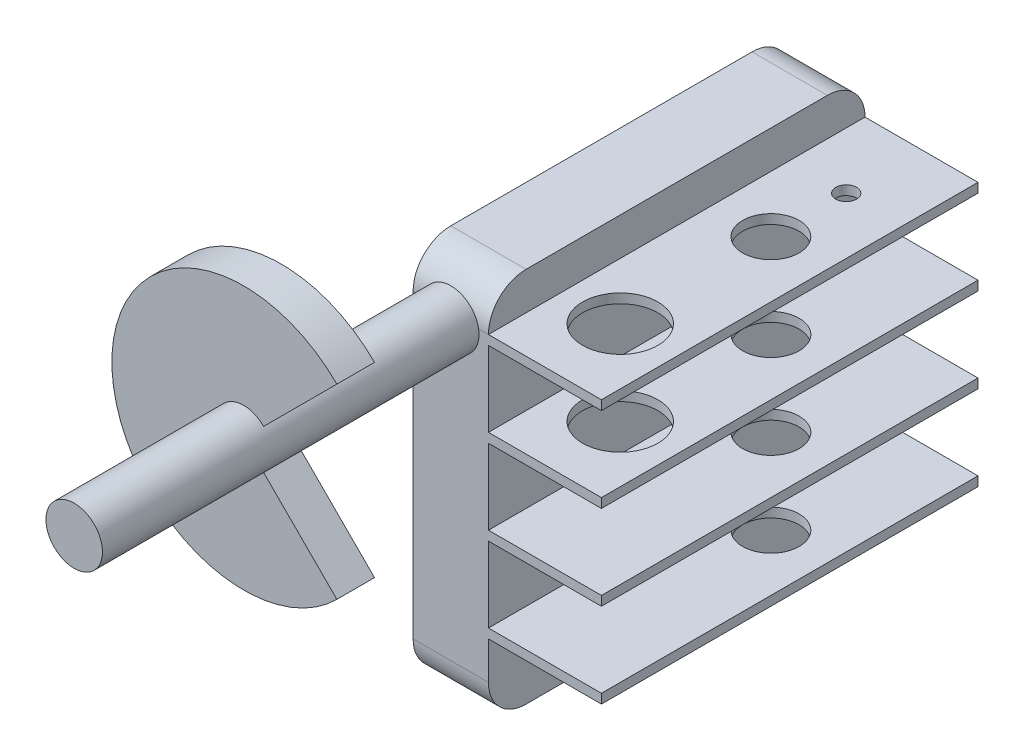
SolidWorks part; units mm, degrees
ref_plane "Front Plane" through (0, 0, 0) normal (0, 0, 1) x (1, 0, 0)
ref_plane "Top Plane" through (0, 0, 0) normal (0, 1, 0) x (1, 0, 0)
ref_plane "Right Plane" through (0, 0, 0) normal (1, 0, 0) x (0, 0, -1)
sketch "Sketch1" plane through (0, 0, 0) normal (0, 0, 1) x (1, 0, 0)
  line L0 (0, 0) -> (0, 10)
  line L1 (0, 10) -> (2, 10)
  line L2 (2, 10) -> (2, 9)
  line L3 (2, 0) -> (0, 0)
  line L4 (2, 8.75) -> (2, 6.75)
  line L5 (2, 9) -> (5, 9)
  line L7 (2, 8.75) -> (5, 8.75)
  line L8 (5, 9) -> (5, 8.75)
  line L9 (2, 6.75) -> (5, 6.75)
  line L11 (2, 6.5) -> (5, 6.5)
  line L12 (5, 6.75) -> (5, 6.5)
  line L13 (2, 4.5) -> (5, 4.5)
  line L15 (2, 4.25) -> (5, 4.25)
  line L16 (5, 4.5) -> (5, 4.25)
  line L17 (2, 2.25) -> (5, 2.25)
  line L19 (2, 2) -> (5, 2)
  line L20 (5, 2.25) -> (5, 2)
  line L21 (2, 6.5) -> (2, 4.5)
  line L22 (2, 4.25) -> (2, 2.25)
  line L23 (2, 2) -> (2, 0)
  dimension "D1" = 10
  dimension "D2" = 2
  dimension "D3" = 3
  dimension "D4" = 0.25
  dimension "D5" = 2
  dimension "D6" = 2
  dimension "D7" = 2
  dimension "D8" = 2
extrude "Boss-Extrude1" add sketch "Sketch1" along normal blind 10
fillet "Fillet1" radius 1 4 edges at (1, 0, 10) (1, 0, 0) (1, 10, 0) (1, 10, 10)
sketch "Sketch2" plane through (0, 0, 10) normal (0, 0, 1) x (1, 0, 0)
  line L0 (0, 9) -> (0, 1) construction
  circle A0 centre (1, 8.8715) radius 0.75
  point P4 (1, 8.2801)
  point P5 (1, 8.8302)
  point P6 (1, 9.1466)
  point P7 (1, 8.8715)
  dimension "D1" = 1
extrude "Boss-Extrude2" add sketch "Sketch2" along normal blind 10
ref_plane "Plane2" through (0, 0, 14.5) normal (0, 0, 1) x (1, 0, 0)
sketch "Sketch3" plane through (0, 0, 14.5) normal (0, 0, 1) x (1, 0, 0)
  line L0 (1, 8.8715) -> (3.4749, 11.3464)
  line L1 (1, 8.8715) -> (3.4749, 6.3966)
  arc A0 (3.4749, 11.3464) -> (3.4749, 6.3966) centre (1, 8.8715) ccw
extrude "Boss-Extrude3" add sketch "Sketch3" along normal blind 1
hole_wizard "Ø0.55 (0.55) Diameter Hole1" positions "3DSketch1" profile "Sketch4" hole size "Ø0.55" standard "ANSI Metric"
sketch3d "3DSketch1"
  line L0 (5, 9, 0) -> (2, 9, 0) construction
  line L1 (5, 9, 10) -> (5, 9, 0) construction
  point P0 (3.5, 9, 2)
  point P8 (0, 0, 0)
  dimension "D1" = 2
  dimension "D2" = 1.5
sketch "Sketch4" plane through (3.5, 9, 2) normal (1, 0, 0) x (0, 0, 1)
  line L0 (0, 0) -> (0, 0.25)
  line L1 (0, 0.25) -> (0.275, 0.25)
  line L2 (0.275, 0.25) -> (0.275, 0)
  line L5 (0.275, 0) -> (0, 0)
  line L11 (0, -6.35) -> (0, 107.95) construction
  dimension "Thru Hole Dia." = 0.55
  dimension "Thru Hole Depth" = 0.25
hole_wizard "Ø1.5 (1.5) Diameter Hole1" positions "Sketch5" profile "Sketch6" hole size "Ø1.5" standard "ANSI Metric" end condition through all
sketch "Sketch5" plane through (0, 9, 0) normal (0, 1, 0) x (1, 0, 0)
  line L0 (5, 0) -> (2, 0) construction
  line L1 (5, -10) -> (5, 0) construction
  point P0 (3.5, -4)
  point P5 (0, 0)
  dimension "D1" = 4
  dimension "D2" = 1.5
sketch "Sketch6" plane through (3.5, 9, 4) normal (1, 0, 0) x (0, 0, 1)
  line L0 (0, 0) -> (0, 9)
  line L1 (0, 9) -> (0.75, 9)
  line L2 (0.75, 9) -> (0.75, 0)
  line L5 (0.75, 0) -> (0, 0)
  line L11 (0, -6.35) -> (0, 107.95) construction
  dimension "Thru Hole Dia." = 1.5
  dimension "Thru Hole Depth" = 9
hole_wizard "Ø2.0mm Dowel Hole1" positions "Sketch7" profile "Sketch8" hole size "Ø2.0" standard "ANSI Metric"
sketch "Sketch7" plane through (0, 9, 0) normal (0, 1, 0) x (1, 0, 0)
  line L0 (5, 0) -> (2, 0) construction
  line L1 (5, -10) -> (5, 0) construction
  point P0 (3.5, -8)
  dimension "D1" = 8
  dimension "D2" = 1.5
sketch "Sketch8" plane through (3.5, 9, 8) normal (1, 0, 0) x (0, 0, 1)
  line L0 (0, 0) -> (0, 5.0999)
  line L1 (0, 5.0999) -> (1, 4.499)
  line L2 (1, 4.499) -> (1, 0)
  line L5 (1, 0) -> (0, 0)
  line L10 (0, 5.0999) -> (-1, 4.499) construction
  line L11 (0, -6.35) -> (0, 107.95) construction
  dimension "Hole Dia." = 2
  dimension "Hole Depth" = 4.499
  dimension "Drill Angle" = 118
